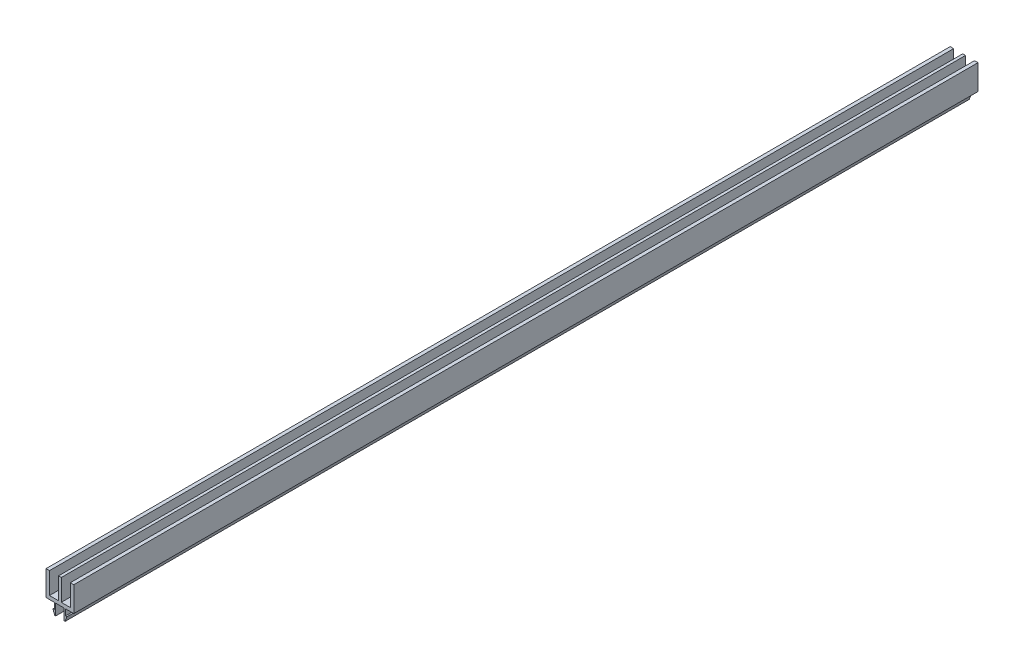
SolidWorks part; units mm, degrees
ref_plane "Plan de face" through (0, 0, 0) normal (0, 0, 1) x (1, 0, 0)
ref_plane "Plan de dessus" through (0, 0, 0) normal (0, 1, 0) x (1, 0, 0)
ref_plane "Plan de droite" through (0, 0, 0) normal (1, 0, 0) x (0, 0, -1)
ref_plane "Plan1" through (0, 0, 50) normal (0, 0, 1) x (1, 0, 0)
sketch "Esquisse1" plane through (0, 0, 50) normal (0, 0, 1) x (1, 0, 0)
  line L0 (-1, 2.5) -> (-7.5, 2.5)
  line L1 (-7.5, 2.5) -> (-7.5, 18)
  line L2 (-7.5, 18) -> (-10, 18)
  line L3 (-10, 18) -> (-10, 0)
  line L4 (-10, 0) -> (-4, 0)
  line L5 (-4, 0) -> (-4, -4.5)
  line L6 (-4, -4.5) -> (-5, -4.5)
  line L7 (-5, -4.5) -> (-3.75, -8)
  line L8 (-3.75, -8) -> (-3, -8)
  line L9 (-3, -8) -> (-3, 0)
  line L10 (-3, 0) -> (3, 0)
  line L11 (3, 0) -> (3, -8)
  line L12 (3, -8) -> (3.75, -8)
  line L13 (3.75, -8) -> (5, -4.5)
  line L14 (5, -4.5) -> (4, -4.5)
  line L15 (4, -4.5) -> (4, 0)
  line L16 (4, 0) -> (10, 0)
  line L17 (10, 0) -> (10, 18)
  line L18 (10, 18) -> (7.5, 18)
  line L19 (7.5, 18) -> (7.5, 2.5)
  line L20 (7.5, 2.5) -> (1, 2.5)
  line L21 (1, 2.5) -> (1, 18)
  line L22 (1, 18) -> (-1, 18)
  line L23 (-1, 18) -> (-1, 2.5)
extrude "Boss.-Extru.1" add sketch "Esquisse1" against normal blind 650.29
